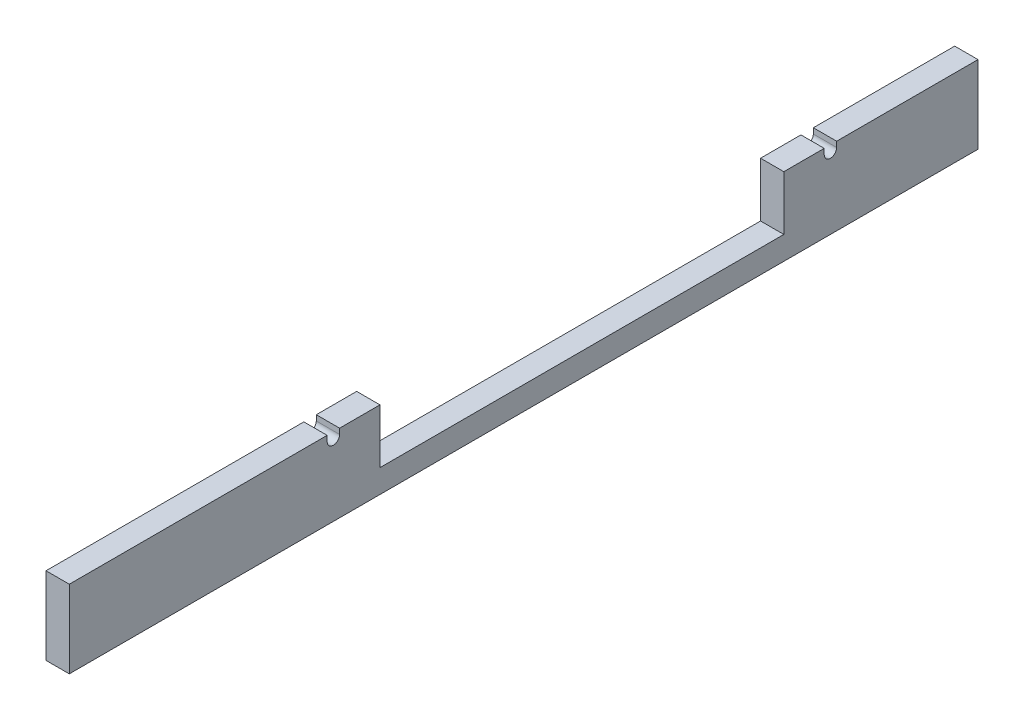
SolidWorks part; units mm, degrees
ref_plane "Alzado" through (0, 0, 0) normal (0, 0, 1) x (1, 0, 0)
ref_plane "Planta" through (0, 0, 0) normal (0, 1, 0) x (1, 0, 0)
ref_plane "Vista lateral" through (0, 0, 0) normal (1, 0, 0) x (0, 0, -1)
sketch "Croquis2" plane through (0, 0, 0) normal (1, 0, 0) x (0, 0, -1)
  line L0 (0, 0) -> (585, 0)
  line L1 (585, 0) -> (585, 50)
  line L2 (585, 50) -> (494, 50)
  line L3 (460, 50) -> (460, 15)
  line L4 (460, 15) -> (200, 15)
  line L5 (200, 15) -> (200, 50)
  line L6 (200, 50) -> (174, 50)
  line L7 (0, 50) -> (0, 0)
  line L8 (166, 50) -> (0, 50)
  line L9 (166, 46.5) -> (166, 50)
  line L10 (174, 46.5) -> (174, 50)
  line L11 (486, 46.5) -> (486, 50)
  line L12 (494, 46.5) -> (494, 50)
  line L13 (486, 50) -> (460, 50)
  line L14 (330, 15) -> (330, 0) construction
  arc A0 (166, 46.5) -> (174, 46.5) centre (170, 46.5) ccw
  arc A1 (486, 46.5) -> (494, 46.5) centre (490, 46.5) ccw
  dimension "D6" = 8
  dimension "D1" = 330
  dimension "D2" = 15
  dimension "D3" = 50
  dimension "D4" = 160
  dimension "D5" = 160
  dimension "D7" = 46.5
  dimension "D8" = 30
  dimension "D9" = 30
  dimension "D10" = 585
extrude "Saliente-Extruir3" add sketch "Croquis2" along normal blind 15
